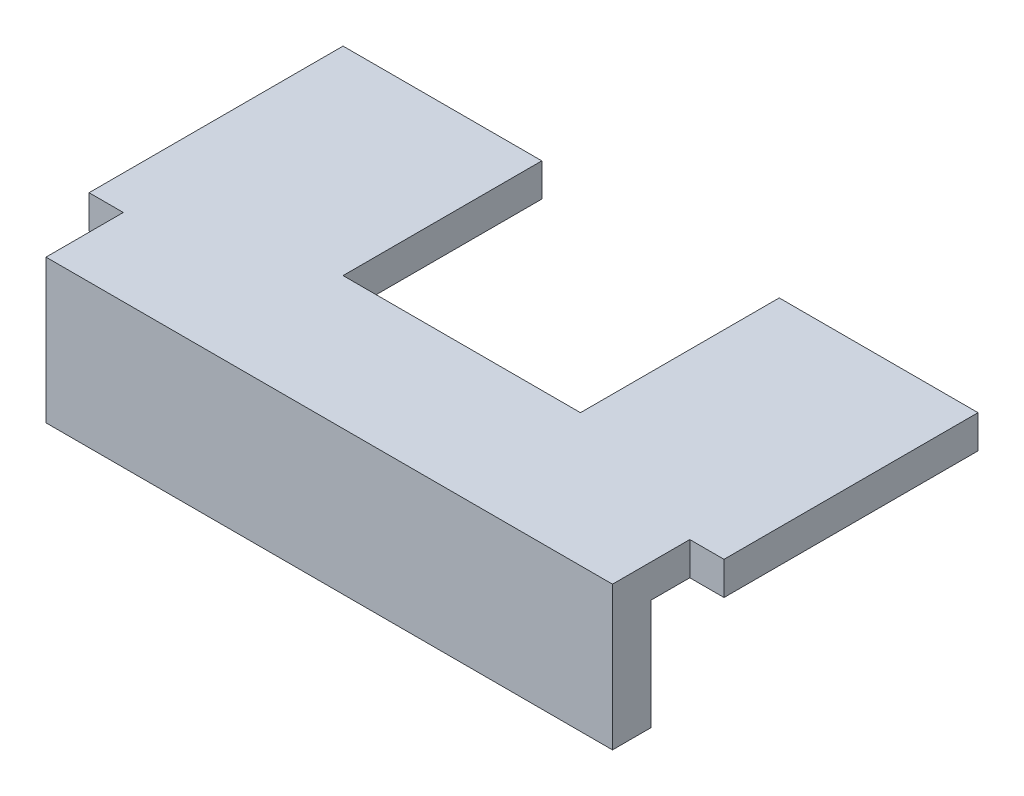
SolidWorks part; units mm, degrees
ref_plane "Front Plane" through (0, 0, 0) normal (0, 0, 1) x (1, 0, 0)
ref_plane "Top Plane" through (0, 0, 0) normal (0, 1, 0) x (1, 0, 0)
ref_plane "Right Plane" through (0, 0, 0) normal (1, 0, 0) x (0, 0, -1)
sketch "Sketch2" plane through (0, 0, 0) normal (0, 1, 0) x (1, 0, 0)
  line L0 (25.65, 0) -> (-25.65, 0)
  line L1 (-25.65, 0) -> (-25.65, 7)
  line L2 (-25.65, 7) -> (-28.75, 7)
  line L3 (-28.75, 7) -> (-28.75, 30)
  line L4 (-28.75, 30) -> (-10.75, 30)
  line L5 (-10.75, 30) -> (-10.75, 12)
  line L6 (-10.75, 12) -> (10.75, 12)
  line L7 (0, 12) -> (0, 0)
  line L8 (28.75, 30) -> (10.75, 30)
  line L9 (25.65, 7) -> (28.75, 7)
  line L10 (10.75, 30) -> (10.75, 12)
  line L11 (28.75, 7) -> (28.75, 30)
  line L12 (25.65, 0) -> (25.65, 7)
  point P4 (0, 0)
  dimension "D1" = 57.5
  dimension "D2" = 3.1
  dimension "D3" = 7
  dimension "D4" = 12
  dimension "D5" = 18
  dimension "D6" = 30
extrude "Boss-Extrude1" add sketch "Sketch2" along normal blind 3 contours L7 L6 L5 L4 L3 L2 L1 L0 | L0 L12 L9 L11 L8 L10 L6 L7
sketch "Sketch3" plane through (0, 0, 0) normal (0, -1, 0) x (1, 0, 0)
  line L0 (25.65, 0) -> (25.65, -7) construction
  line L1 (-25.65, 0) -> (25.65, 0)
  line L2 (-25.65, 0) -> (-25.65, -3.5)
  line L3 (-25.65, -3.5) -> (25.65, -3.5)
  line L4 (25.65, 0) -> (25.65, -3.5)
extrude "Boss-Extrude2" add sketch "Sketch3" along normal blind 10
